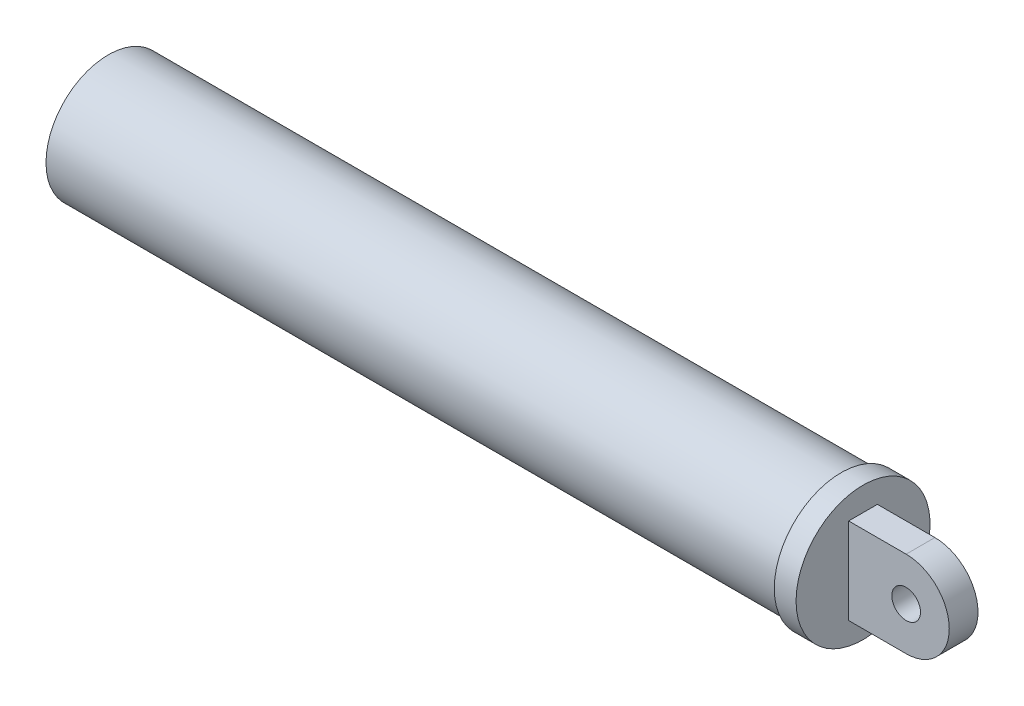
SolidWorks part; units mm, degrees
ref_plane "Front Plane" through (0, 0, 0) normal (0, 0, 1) x (1, 0, 0)
ref_plane "Top Plane" through (0, 0, 0) normal (0, 1, 0) x (1, 0, 0)
ref_plane "Right Plane" through (0, 0, 0) normal (1, 0, 0) x (0, 0, -1)
sketch "Sketch1" plane through (0, 0, 0) normal (0, 0, 1) x (1, 0, 0)
  line L1 (299.5682, 38.9816) -> (319.5682, 38.9816)
  line L2 (299.5682, 38.9816) -> (299.5682, 8.9816)
  line L3 (299.5682, 8.9816) -> (319.5682, 8.9816)
  circle A0 centre (319.5682, 23.9816) radius 4.9933
  arc A1 (319.5682, 8.9816) -> (319.5682, 38.9816) centre (319.5682, 23.9816) ccw
  dimension "D1" = 30
  dimension "D2" = 20
extrude "Boss-Extrude2" add sketch "Sketch1" along normal mid plane 10
sketch "Sketch3" plane through (0, 0, 0) normal (0, 0, 1) x (1, 0, 0)
  line L0 (291.9986, 45.6547) -> (291.9986, 47.2812)
  line L1 (36.9986, 39.6108) -> (36.9986, 45.6547)
  line L2 (291.9986, 47.2812) -> (299.5682, 47.2812)
  line L3 (299.5682, 47.2812) -> (299.5682, 38.9816)
  line L4 (291.9986, 45.6547) -> (36.9986, 45.6547)
  line L6 (36.9986, 39.6108) -> (286.9986, 39.6108)
  line L7 (286.9986, 39.6108) -> (286.9986, 23.9816)
  line L8 (286.9986, 23.9816) -> (299.5682, 23.9816)
  line L9 (299.5682, 38.9816) -> (299.5682, 8.9816) construction
  line L10 (299.5682, 38.9816) -> (299.5682, 23.9816)
  dimension "D1" = 5
  dimension "D4" = 250
revolve "Revolve3" add sketch "Sketch3" angle 360 about L8
